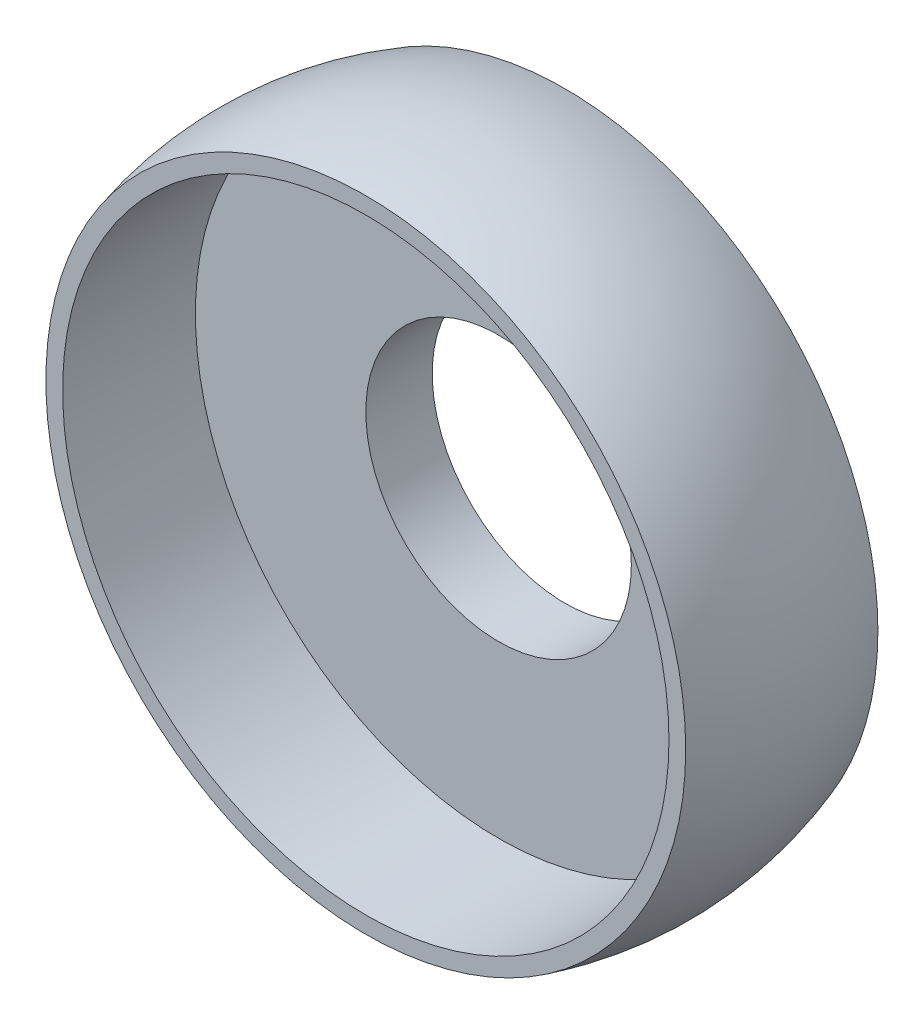
SolidWorks part; units mm, degrees
ref_plane "前视基准面" through (0, 0, 0) normal (0, 0, 1) x (1, 0, 0)
ref_plane "上视基准面" through (0, 0, 0) normal (0, 1, 0) x (1, 0, 0)
ref_plane "右视基准面" through (0, 0, 0) normal (1, 0, 0) x (0, 0, -1)
sketch "草图1" plane through (0, 0, 0) normal (0, 0, 1) x (1, 0, 0)
  line L0 (-7.5, 0) -> (7.5, 0) construction
  line L1 (-7.5, 0) -> (7.5, 0)
  arc A0 (7.5, 0) -> (-7.5, 0) centre (0, 0) ccw
  dimension "D1" = 15
revolve "旋转2" add sketch "草图1" angle 360 about L0
ref_plane "基准面1" through (0, 0, 2) normal (0, 0, 1) x (1, 0, 0)
sketch "草图4" plane through (0, 0, 2) normal (0, 0, 1) x (1, 0, 0)
  circle A0 centre (0, 0) radius 9.7624
extrude "切除-拉伸1" cut sketch "草图4" along normal through all
sketch "草图5" plane through (0, 0, 2) normal (0, 0, 1) x (1, 0, 0)
  circle A0 centre (0, 0) radius 6.85
  dimension "D1" = 13.7
extrude "切除-拉伸2" cut sketch "草图5" against normal blind 3
sketch "草图7" plane through (0, 0, -1) normal (0, 0, 1) x (1, 0, 0)
  circle A0 centre (0, 0) radius 3
  dimension "D1" = 6
extrude "切除-拉伸3" cut sketch "草图7" against normal through all and the other way through all
ref_plane "基准面2" through (0, 0, -2.5) normal (0, 0, 1) x (1, 0, 0)
sketch "草图8" plane through (0, 0, -2.5) normal (0, 0, 1) x (1, 0, 0)
  circle A0 centre (0, 0) radius 10.1691
extrude "切除-拉伸4" cut sketch "草图8" against normal through all
sketch "草图10" plane through (0, 0, 0) normal (1, 0, 0) x (0, 0, -1)
  line L0 (-2, 0) -> (2.5, 0)
  line L1 (-2, 7.2284) -> (-2, -7.2284) construction
  line L2 (2.5, -7.0711) -> (2.5, 7.0711) construction
  line L3 (2.5, 0) -> (2.5, 7.0711)
  line L4 (-2, 0) -> (-2, 7.2284)
  arc A0 (2.5, 7.0711) -> (-2, 7.2284) centre (0, 0) ccw
